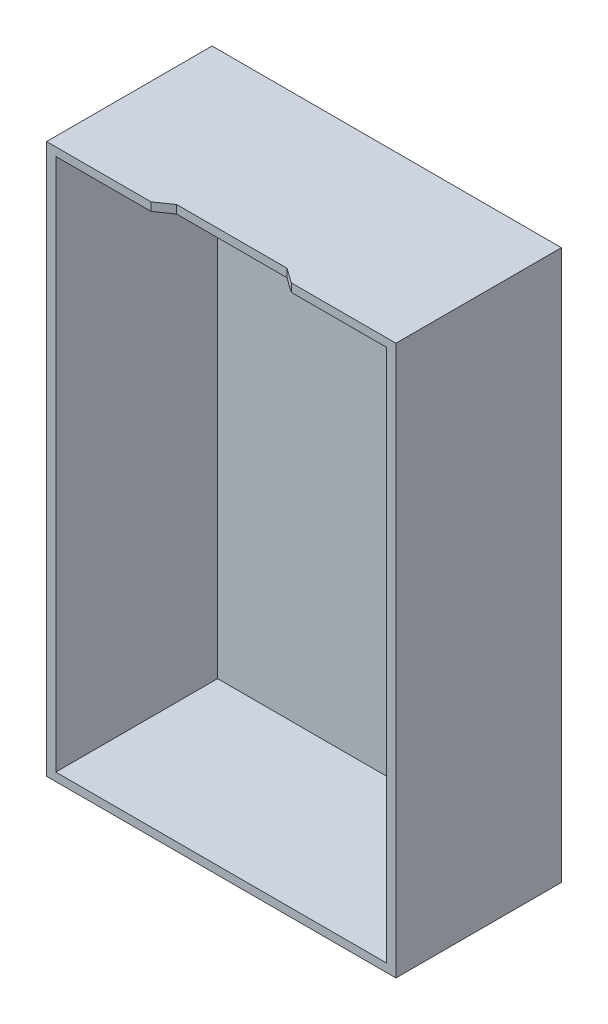
SolidWorks part; units mm, degrees
ref_plane "Front Plane" through (0, 0, 0) normal (0, 0, 1) x (1, 0, 0)
ref_plane "Top Plane" through (0, 0, 0) normal (0, 1, 0) x (1, 0, 0)
ref_plane "Right Plane" through (0, 0, 0) normal (1, 0, 0) x (0, 0, -1)
sketch "Sketch1" plane through (0, 0, 0) normal (0, 1, 0) x (1, 0, 0)
  line L1 (-120.65, 57.15) -> (120.65, 57.15)
  line L2 (-120.65, 57.15) -> (-120.65, -57.15)
  line L3 (-120.65, -57.15) -> (120.65, -57.15)
  line L4 (120.65, 57.15) -> (120.65, -57.15)
  line L5 (-120.65, 57.15) -> (120.65, -57.15) construction
  line L6 (-120.65, -57.15) -> (120.65, 57.15) construction
  point P0 (0, 0)
  dimension "D1" = 241.3
  dimension "D2" = 114.3
extrude "Boss-Extrude1" add sketch "Sketch1" along normal blind 379.73
sketch "Sketch2" plane through (0, 0, 57.15) normal (0, 0, 1) x (1, 0, 0)
  line L0 (0, 379.73) -> (0, 0) construction
  line L1 (-120.65, 379.73) -> (120.65, 379.73) construction
  line L2 (-120.65, 189.865) -> (120.65, 189.865) construction
  line L3 (-120.65, 379.73) -> (-120.65, 0) construction
  line L4 (120.65, 379.73) -> (120.65, 0) construction
  line L6 (-114.3, 374.015) -> (114.3, 374.015)
  line L7 (-114.3, 374.015) -> (-114.3, 5.715)
  line L8 (-114.3, 5.715) -> (114.3, 5.715)
  line L9 (114.3, 374.015) -> (114.3, 5.715)
  line L10 (-114.3, 374.015) -> (114.3, 5.715) construction
  line L11 (-114.3, 5.715) -> (114.3, 374.015) construction
  point P11 (0, 189.865)
  dimension "D1" = 368.3
  dimension "D2" = 228.6
extrude "Cut-Extrude1" cut sketch "Sketch2" against normal blind 111.76
sketch "Sketch3" plane through (0, 379.73, 0) normal (0, 1, 0) x (1, 0, 0)
  line L0 (-38.1, -49.8836) -> (-48.5109, -57.15)
  line L7 (-120.65, -57.15) -> (120.65, -57.15) construction
  line L8 (-38.1, -49.8836) -> (38.1, -49.8836)
  line L9 (38.1, -49.8836) -> (48.3848, -57.15)
  line L10 (48.3848, -57.15) -> (-48.5109, -57.15)
  point P10 (0, 49.8836)
extrude "Cut-Extrude2" cut sketch "Sketch3" against normal blind 111.76
